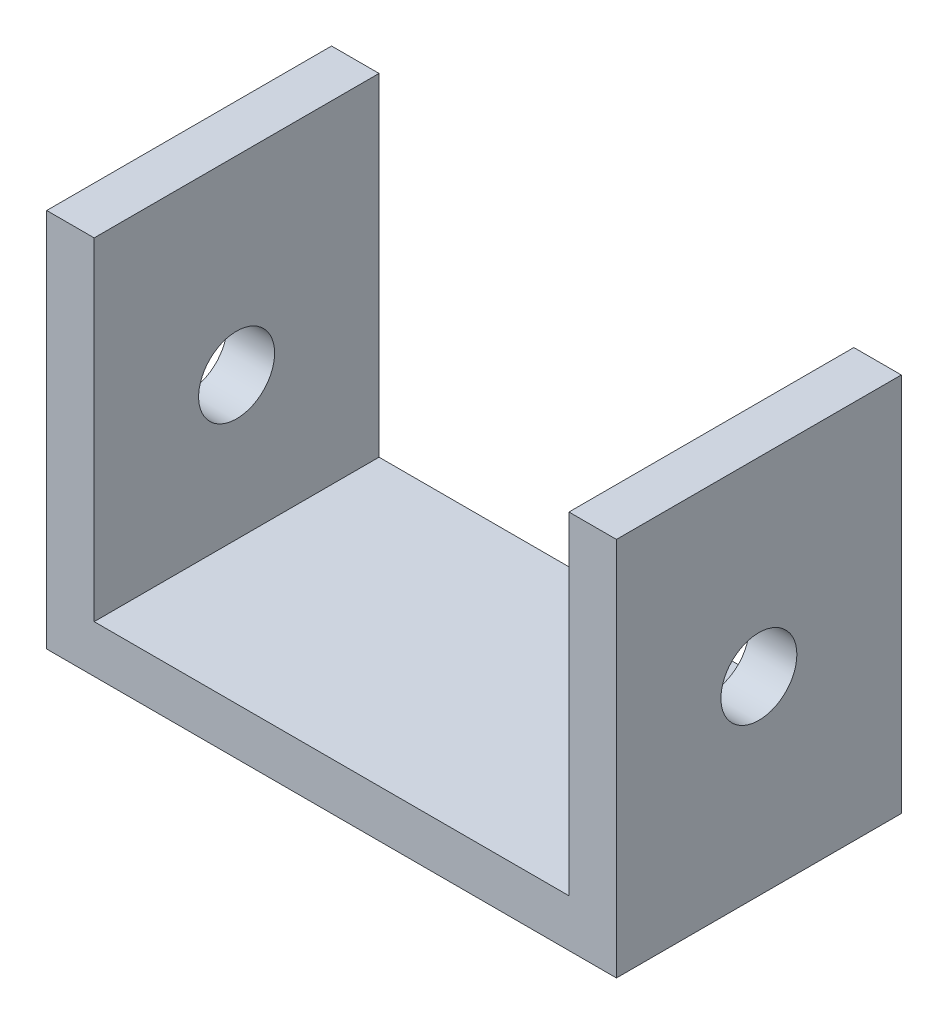
SolidWorks part; units mm, degrees
material "AISI 1020"
ref_plane "Front Plane" through (0, 0, 0) normal (0, 0, 1) x (1, 0, 0)
ref_plane "Top Plane" through (0, 0, 0) normal (0, 1, 0) x (1, 0, 0)
ref_plane "Right Plane" through (0, 0, 0) normal (1, 0, 0) x (0, 0, -1)
sketch "Sketch2" plane through (0, 0, 0) normal (0, 1, 0) x (1, 0, 0)
  line L1 (-60, 30) -> (60, 30)
  line L2 (-60, 30) -> (-60, -30)
  line L3 (-60, -30) -> (60, -30)
  line L4 (60, 30) -> (60, -30)
  line L5 (-60, 30) -> (60, -30) construction
  line L6 (-60, -30) -> (60, 30) construction
  point P0 (0, 0)
  dimension "D1" = 120
  dimension "D2" = 60
extrude "Base" add sketch "Sketch2" along normal blind 10
sketch "Sketch5" plane through (0, 10, 0) normal (0, 1, 0) x (1, 0, 0)
  line L0 (60, 30) -> (-60, 30) construction
  line L1 (50, -30) -> (60, -30)
  line L2 (50, -30) -> (50, 30)
  line L3 (50, 30) -> (60, 30)
  line L4 (60, -30) -> (60, 30)
  line L5 (50, -30) -> (60, 30) construction
  line L6 (50, 30) -> (60, -30) construction
  line L7 (60, -30) -> (60, 30) construction
  point P0 (55, 0)
  dimension "D1" = 10
extrude "Upright" add sketch "Sketch5" along normal blind 70
sketch "Sketch6" plane through (60, 0, 0) normal (1, 0, 0) x (0, 0, -1)
  line L0 (-30, 80) -> (-30, 0) construction
  line L1 (30, 80) -> (30, 0) construction
  circle A0 centre (0, 40) radius 8
  dimension "D1" = 40
  dimension "D2" = 16
  dimension "D3" = 30
  dimension "D4" = 30
extrude "Shaft Hole" cut sketch "Sketch6" against normal blind 50
mirror "Mirror" about plane through (0, 0, 0) normal (1, 0, 0) of bodies 103
